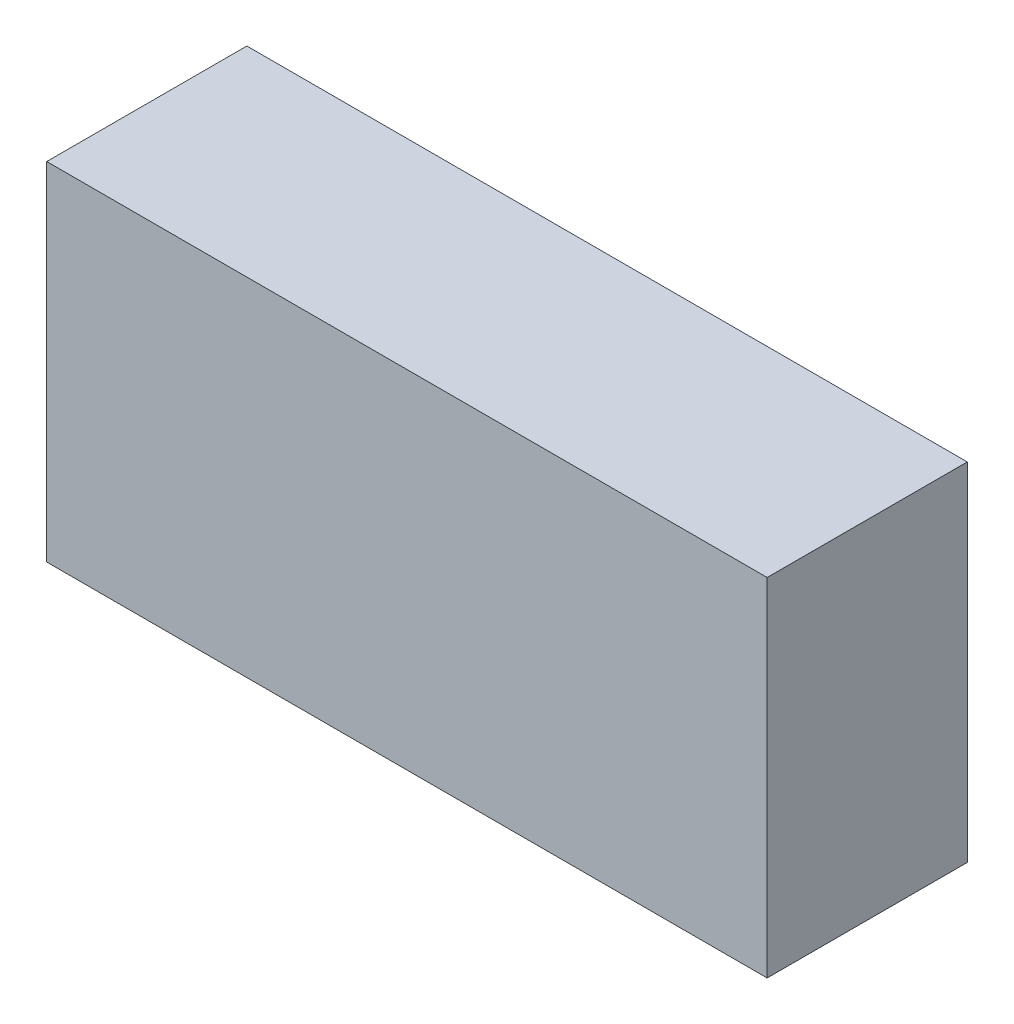
SolidWorks part; units mm, degrees
ref_plane "Front Plane" through (0, 0, 0) normal (0, 0, 1) x (1, 0, 0)
ref_plane "Top Plane" through (0, 0, 0) normal (0, 1, 0) x (1, 0, 0)
ref_plane "Right Plane" through (0, 0, 0) normal (1, 0, 0) x (0, 0, -1)
sketch "Controller and connector envelope profile" plane through (0, 0, 0) normal (0, 0, 1) x (1, 0, 0)
  line L0 (-27, -13) -> (27, -13)
  line L1 (27, -13) -> (27, 13)
  line L2 (27, 13) -> (-27, 13)
  line L3 (-27, 13) -> (-27, -13)
extrude "Controller and connector envelope" add sketch "Controller and connector envelope profile" along normal blind 15
